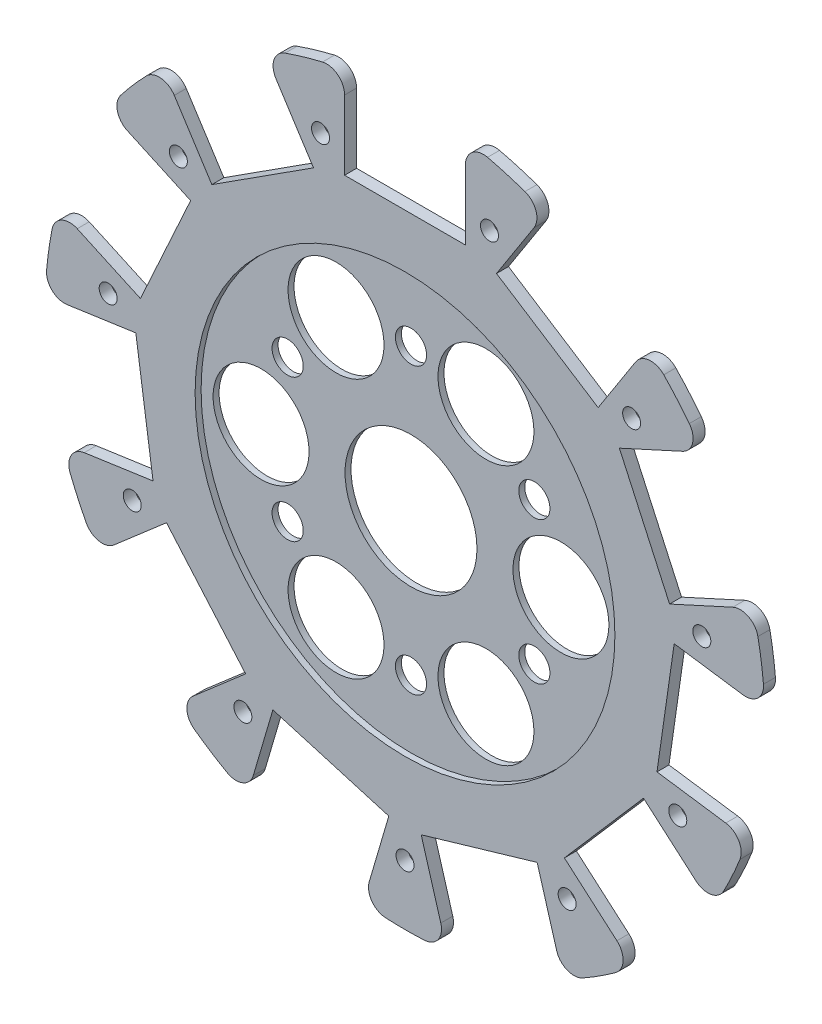
SolidWorks part; units mm, degrees
ref_plane "Front Plane" through (0, 0, 0) normal (0, 0, 1) x (1, 0, 0)
ref_plane "Top Plane" through (0, 0, 0) normal (0, 1, 0) x (1, 0, 0)
ref_plane "Right Plane" through (0, 0, 0) normal (1, 0, 0) x (0, 0, -1)
sketch "Sketch1" plane through (0, 0, 0) normal (0, 0, 1) x (1, 0, 0)
  line L44 (21.5207, 52.1193) -> (15.2567, 42.3722)
  line L47 (-10.0734, 55.4805) -> (-10.0734, 43.8941)
  line L48 (-10.0734, 43.8941) -> (10.0734, 43.8941)
  line L49 (10.0734, 55.4805) -> (10.0734, 43.8941)
  line L51 (38.4693, 41.2271) -> (32.2052, 31.48)
  line L52 (15.2567, 42.3722) -> (32.2052, 31.48)
  line L53 (46.2822, 32.2105) -> (35.7428, 27.3974)
  line L55 (54.6515, 13.8844) -> (44.1121, 9.0712)
  line L56 (35.7428, 27.3974) -> (44.1121, 9.0712)
  line L57 (56.3494, 2.0752) -> (44.8809, 3.7241)
  line L59 (53.4822, -17.8666) -> (42.0137, -16.2176)
  line L60 (44.8809, 3.7241) -> (42.0137, -16.2176)
  line L61 (48.526, -28.719) -> (39.7696, -21.1316)
  line L63 (35.3327, -43.945) -> (26.5763, -36.3575)
  line L64 (39.7696, -21.1316) -> (26.5763, -36.3575)
  line L65 (25.296, -50.3952) -> (22.0318, -39.2781)
  line L67 (5.9653, -56.0712) -> (2.701, -44.9541)
  line L68 (22.0318, -39.2781) -> (2.701, -44.9541)
  line L69 (-5.9653, -56.0712) -> (-2.701, -44.9541)
  line L71 (-25.296, -50.3952) -> (-22.0318, -39.2781)
  line L72 (-2.701, -44.9541) -> (-22.0318, -39.2781)
  line L73 (-35.3327, -43.945) -> (-26.5763, -36.3575)
  line L75 (-48.526, -28.719) -> (-39.7696, -21.1316)
  line L76 (-26.5763, -36.3575) -> (-39.7696, -21.1316)
  line L77 (-53.4822, -17.8666) -> (-42.0137, -16.2176)
  line L79 (-56.3494, 2.0752) -> (-44.8809, 3.7241)
  line L80 (-42.0137, -16.2176) -> (-44.8809, 3.7241)
  line L81 (-54.6515, 13.8844) -> (-44.1121, 9.0712)
  line L83 (-46.2822, 32.2105) -> (-35.7428, 27.3974)
  line L84 (-44.1121, 9.0712) -> (-35.7428, 27.3974)
  line L85 (-38.4693, 41.2271) -> (-32.2052, 31.48)
  line L87 (-21.5207, 52.1193) -> (-15.2567, 42.3722)
  line L88 (-32.2052, 31.48) -> (-15.2567, 42.3722)
  arc A33 (-43.1506, 41.6896) -> (-47.4063, 36.7783) centre (0, 0) ccw
  arc A34 (-13.7615, 58.4005) -> (-19.9968, 56.5697) centre (0, 0) ccw
  arc A35 (19.9968, 56.5697) -> (13.7615, 58.4005) centre (0, 0) ccw
  arc A36 (47.4063, 36.7783) -> (43.1506, 41.6896) centre (0, 0) ccw
  arc A37 (59.7646, 5.3101) -> (58.8397, 11.7426) centre (0, 0) ccw
  arc A38 (53.148, -27.844) -> (55.8476, -21.9327) centre (0, 0) ccw
  arc A39 (29.6574, -52.1578) -> (35.1243, -48.6444) centre (0, 0) ccw
  arc A40 (-3.2493, -59.912) -> (3.2493, -59.912) centre (0, 0) ccw
  arc A41 (-35.1243, -48.6444) -> (-29.6574, -52.1578) centre (0, 0) ccw
  arc A42 (-55.8476, -21.9327) -> (-53.148, -27.844) centre (0, 0) ccw
  arc A43 (-58.8397, 11.7426) -> (-59.7646, 5.3101) centre (0, 0) ccw
  arc A44 (-54.6515, 13.8844) -> (-58.8397, 11.7426) centre (-55.8977, 11.1555) ccw
  arc A45 (-56.3494, 2.0752) -> (-59.7646, 5.3101) centre (-56.7763, 5.0446) cw
  arc A46 (-48.526, -28.719) -> (-53.148, -27.844) centre (-50.4906, -26.4518) cw
  arc A47 (-53.4822, -17.8666) -> (-55.8476, -21.9327) centre (-53.0553, -20.836) ccw
  arc A48 (-25.296, -50.3952) -> (-29.6574, -52.1578) centre (-28.1745, -49.55) cw
  arc A49 (-35.3327, -43.945) -> (-35.1243, -48.6444) centre (-33.3681, -46.2122) ccw
  arc A50 (-5.9653, -56.0712) -> (-3.2493, -59.912) centre (-3.0868, -56.9164) ccw
  arc A51 (5.9653, -56.0712) -> (3.2493, -59.912) centre (3.0868, -56.9164) cw
  arc A52 (35.3327, -43.945) -> (35.1243, -48.6444) centre (33.3681, -46.2122) cw
  arc A53 (25.296, -50.3952) -> (29.6574, -52.1578) centre (28.1745, -49.55) ccw
  arc A54 (48.526, -28.719) -> (53.148, -27.844) centre (50.4906, -26.4518) ccw
  arc A55 (53.4822, -17.8666) -> (55.8476, -21.9327) centre (53.0553, -20.836) cw
  arc A56 (56.3494, 2.0752) -> (59.7646, 5.3101) centre (56.7763, 5.0446) ccw
  arc A57 (54.6515, 13.8844) -> (58.8397, 11.7426) centre (55.8977, 11.1555) cw
  arc A58 (46.2822, 32.2105) -> (47.4063, 36.7783) centre (45.036, 34.9394) ccw
  arc A59 (38.4693, 41.2271) -> (43.1506, 41.6896) centre (40.9931, 39.6052) cw
  arc A60 (21.5207, 52.1193) -> (19.9968, 56.5697) centre (18.997, 53.7412) ccw
  arc A61 (10.0734, 55.4805) -> (13.7615, 58.4005) centre (13.0734, 55.4805) cw
  arc A62 (-10.0734, 55.4805) -> (-13.7615, 58.4005) centre (-13.0734, 55.4805) ccw
  arc A63 (-21.5207, 52.1193) -> (-19.9968, 56.5697) centre (-18.997, 53.7412) cw
  arc A64 (-38.4693, 41.2271) -> (-43.1506, 41.6896) centre (-40.9931, 39.6052) ccw
  arc A65 (-46.2822, 32.2105) -> (-47.4063, 36.7783) centre (-45.036, 34.9394) cw
  point P3 (-57.9879, 15.408)
  point P51 (0, 0)
  point P55 (-57.1127, -18.3885)
  point P60 (-38.1047, -46.3469)
  point P63 (-6.9987, -59.5904)
  point P70 (26.3294, -53.9144)
  point P73 (51.298, -31.121)
  point P78 (59.9799, 1.5532)
  point P83 (49.6186, 33.7342)
  point P88 (23.5037, 55.2048)
  point P93 (-10.0734, 59.1483)
  dimension "D1" = 120
  dimension "D2" = 3
extrude "Boss-Extrude1" add sketch "Sketch1" along normal blind 2
sketch "Sketch2" plane through (0, 0, 2) normal (0, 0, 1) x (1, 0, 0)
  circle A0 centre (0, 0) radius 35
  dimension "D1" = 70
extrude "Cut-Extrude1" cut sketch "Sketch2" against normal blind 1
sketch "Sketch3" plane through (0, 0, 1) normal (0, 0, 1) x (1, 0, 0)
  line L0 (0, 0) -> (0, 14.7126) construction
  line L1 (0, 0) -> (-12.5, 21.6506) construction
  circle A0 centre (0, 0) radius 11
  circle A1 centre (0, 23.75) radius 2.6
  circle A2 centre (20.5681, 11.875) radius 2.6
  circle A3 centre (20.5681, -11.875) radius 2.6
  circle A4 centre (0, -23.75) radius 2.6
  circle A5 centre (-20.5681, -11.875) radius 2.6
  circle A6 centre (-20.5681, 11.875) radius 2.6
  circle A7 centre (-12.5, 21.6506) radius 8
  circle A8 centre (12.5, 21.6506) radius 8
  circle A9 centre (25, 0) radius 8
  circle A10 centre (12.5, -21.6506) radius 8
  circle A11 centre (-12.5, -21.6506) radius 8
  circle A12 centre (-25, 0) radius 8
  point P17 (0, 0)
  point P31 (0, 0)
  dimension "D1" = 22
  dimension "D2" = 5.2
  dimension "D4" = 16
  dimension "D3" = 23.75
  dimension "D5" = 25
  dimension "D6" = 30
extrude "Cut-Extrude2" cut sketch "Sketch3" against normal blind 1
sketch "Sketch4" plane through (0, 0, 2) normal (0, 0, 1) x (1, 0, 0)
  line L0 (0, 17.7708) -> (0, 0) construction
  line L1 (0, 0) -> (-14.0866, 47.9746) construction
  circle A0 centre (-14.0866, 47.9746) radius 1.5
  circle A1 centre (14.0866, 47.9746) radius 1.5
  circle A2 centre (37.7875, 32.743) radius 1.5
  circle A3 centre (49.4911, 7.1157) radius 1.5
  circle A4 centre (45.4816, -20.7708) radius 1.5
  circle A5 centre (27.032, -42.0627) radius 1.5
  circle A6 centre (0, -50) radius 1.5
  circle A7 centre (-27.032, -42.0627) radius 1.5
  circle A8 centre (-45.4816, -20.7708) radius 1.5
  circle A9 centre (-49.4911, 7.1157) radius 1.5
  circle A10 centre (-37.7875, 32.743) radius 1.5
  point P28 (0, 0)
  dimension "D1" = 3
  dimension "D2" = 50
  dimension "D3" = 16.364
extrude "Cut-Extrude3" cut sketch "Sketch4" against normal blind 2
